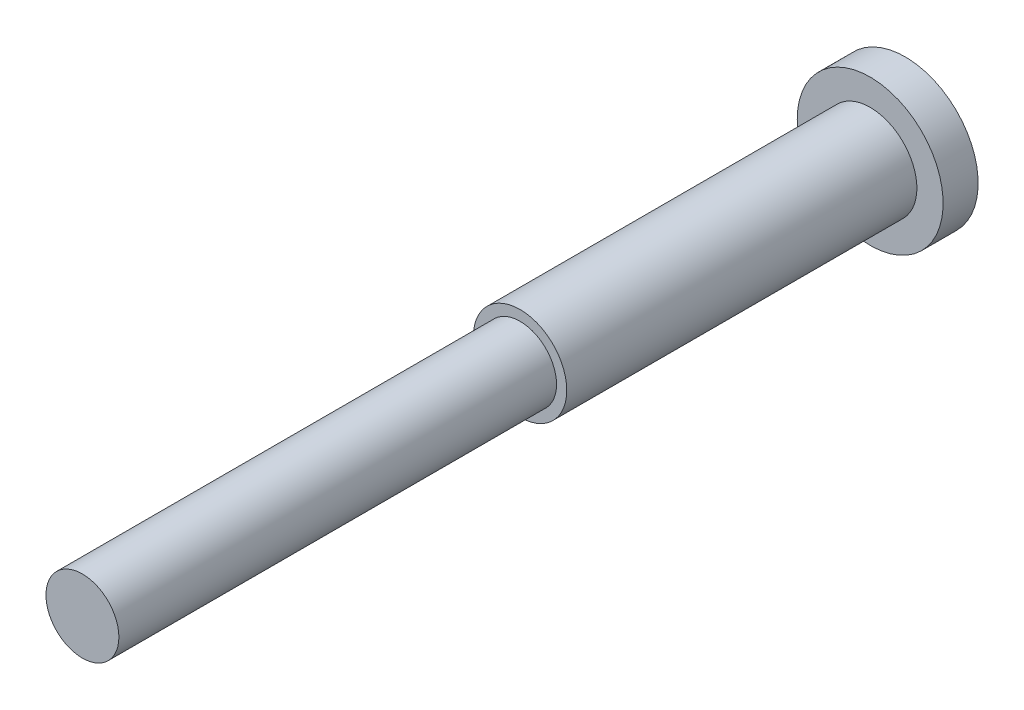
SolidWorks part; units mm, degrees
material "PW20:29:Sc:0:"
ref_plane "Front" through (0, 0, 0) normal (0, 0, 1) x (1, 0, 0)
ref_plane "Top" through (0, 0, 0) normal (0, 1, 0) x (1, 0, 0)
ref_plane "Right" through (0, 0, 0) normal (1, 0, 0) x (0, 0, -1)
other "Configuration Table"
sketch "Sketch1" plane through (0, 0, 0) normal (0, 0, 1) x (1, 0, 0)
  circle A0 centre (0, 0) radius 8
  dimension "D1" = 16
extrude "Base-Extrude" add sketch "Sketch1" along normal blind 60
sketch "Sketch2" plane through (0, 0, 60) normal (0, 0, 1) x (1, 0, 0)
  circle A0 centre (0, 0) radius 6.25
  dimension "D1" = 12.5
extrude "Boss-Extrude1" add sketch "Sketch2" along normal blind 75
sketch "Sketch3" plane through (0, 0, 0) normal (0, 0, -1) x (-1, 0, 0)
  circle A0 centre (0, 0) radius 12.5
  dimension "D1" = 25
extrude "Boss-Extrude2" add sketch "Sketch3" along normal blind 6
ref_plane "Place" through (0, 0, 55) normal (0, 0, 1) x (1, 0, 0)
